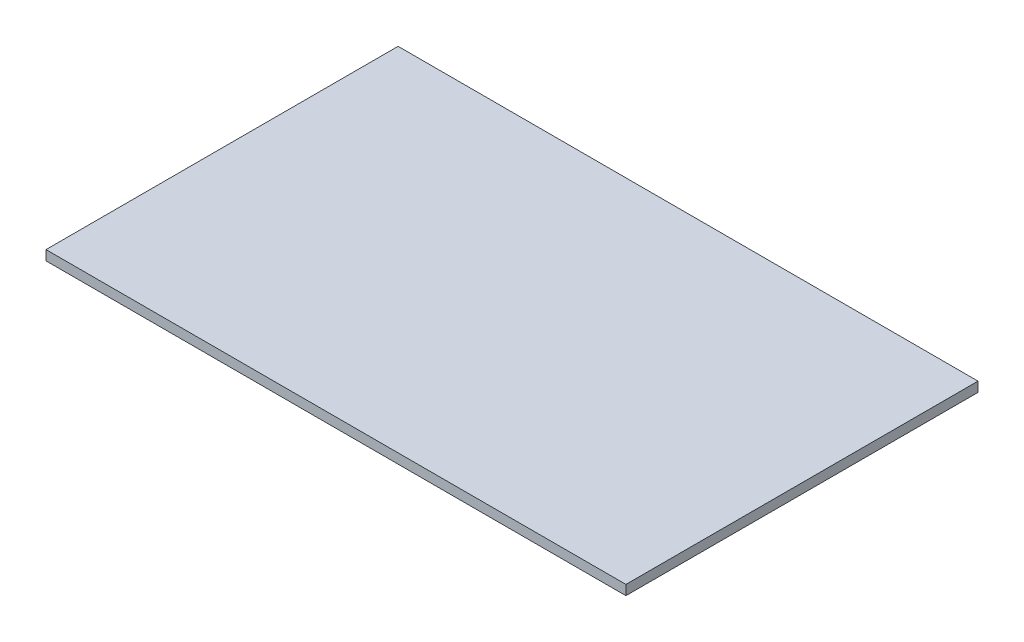
SolidWorks part; units mm, degrees
ref_plane "Front Plane" through (0, 0, 0) normal (0, 0, 1) x (1, 0, 0)
ref_plane "Top Plane" through (0, 0, 0) normal (0, 1, 0) x (1, 0, 0)
ref_plane "Right Plane" through (0, 0, 0) normal (1, 0, 0) x (0, 0, -1)
sketch "Sketch1" plane through (0, 0, 0) normal (0, 1, 0) x (1, 0, 0)
  line L1 (-177.8, -107.95) -> (177.8, -107.95)
  line L2 (-177.8, -107.95) -> (-177.8, 107.95)
  line L3 (-177.8, 107.95) -> (177.8, 107.95)
  line L4 (177.8, -107.95) -> (177.8, 107.95)
  line L5 (-177.8, -107.95) -> (177.8, 107.95) construction
  line L6 (-177.8, 107.95) -> (177.8, -107.95) construction
  point P0 (0, 0)
  dimension "D1" = 355.6
  dimension "D2" = 215.9
extrude "Boss-Extrude1" add sketch "Sketch1" along normal blind 6 contours L2 L3 L4 L1
